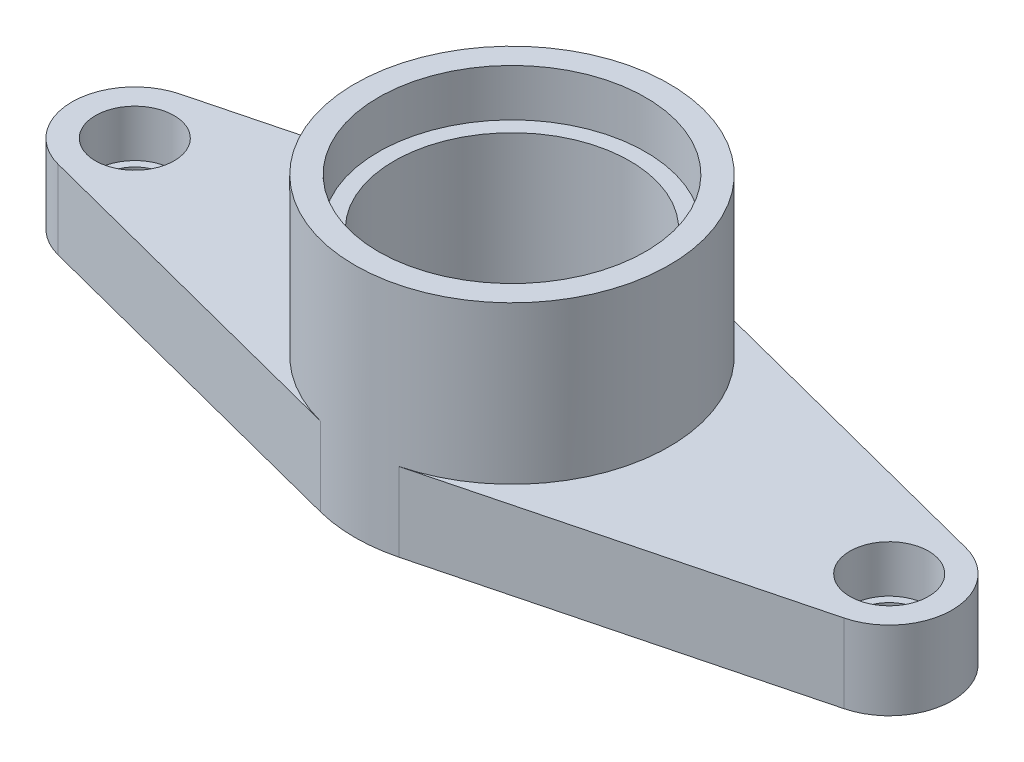
SolidWorks part; units mm, degrees
ref_plane "Front Plane" through (0, 0, 0) normal (0, 0, 1) x (1, 0, 0)
ref_plane "Top Plane" through (0, 0, 0) normal (0, 1, 0) x (1, 0, 0)
ref_plane "Right Plane" through (0, 0, 0) normal (1, 0, 0) x (0, 0, -1)
sketch "Sketch1" plane through (0, 0, 0) normal (0, 1, 0) x (1, 0, 0)
  line L0 (-325.3729, 0) -> (318.7166, 0) construction
  line L1 (-125, 19.3649) -> (-12.5, 48.4123)
  line L2 (0, 164.3244) -> (0, -173.2063) construction
  line L3 (-125, -19.3649) -> (-12.5, -48.4123)
  line L4 (12.5, 48.4123) -> (125, 19.3649)
  line L5 (12.5, -48.4123) -> (125, -19.3649)
  arc A0 (-12.5, -48.4123) -> (12.5, -48.4123) centre (0, 0) ccw
  arc A1 (-125, 19.3649) -> (-125, -19.3649) centre (-120, 0) ccw
  arc A2 (125, -19.3649) -> (125, 19.3649) centre (120, 0) ccw
  arc A3 (12.5, 48.4123) -> (-12.5, 48.4123) centre (0, 0) ccw
  dimension "D1" = 100
  dimension "D2" = 40
  dimension "D3" = 120
extrude "Boss-Extrude1" add sketch "Sketch1" along normal blind 25
sketch "Sketch2" plane through (0, 25, 0) normal (0, 1, 0) x (1, 0, 0)
  circle A0 centre (0, 0) radius 50
  arc A1 (12.5, 48.4123) -> (-12.5, 48.4123) centre (0, 0) ccw construction
extrude "Boss-Extrude2" add sketch "Sketch2" along normal blind 50 contours A0
sketch "Sketch3" plane through (0, 75, 0) normal (0, 1, 0) x (1, 0, 0)
  circle A0 centre (0, 0) radius 42.5
  dimension "D1" = 85
extrude "Cut-Extrude1" cut sketch "Sketch3" against normal blind 15
sketch "Sketch4" plane through (0, 60, 0) normal (0, 1, 0) x (1, 0, 0)
  circle A0 centre (0, 0) radius 37.5
  dimension "D1" = 75
extrude "Cut-Extrude2" cut sketch "Sketch4" against normal through all
sketch "Sketch5" plane through (0, 25, 0) normal (0, 1, 0) x (1, 0, 0)
  line L0 (0, 176.6087) -> (0, -62.5574)
  circle A0 centre (-120, 0) radius 12.5
  arc A2 (-125, 19.3649) -> (-125, -19.3649) centre (-120, 0) ccw construction
  circle A3 centre (120, 0) radius 12.5
  point P11 (0, 57.0256)
  dimension "D1" = 25
extrude "Cut-Extrude3" cut sketch "Sketch5" against normal blind 15 contours A3 | A0
sketch "Sketch6" plane through (0, 25, 0) normal (0, 1, 0) x (1, 0, 0)
  line L0 (0, 61.1256) -> (0, -66.567) construction
  circle A0 centre (-120, 0) radius 10
  circle A1 centre (120, 0) radius 10
  dimension "D1" = 20
extrude "Cut-Extrude4" cut sketch "Sketch6" against normal through all
